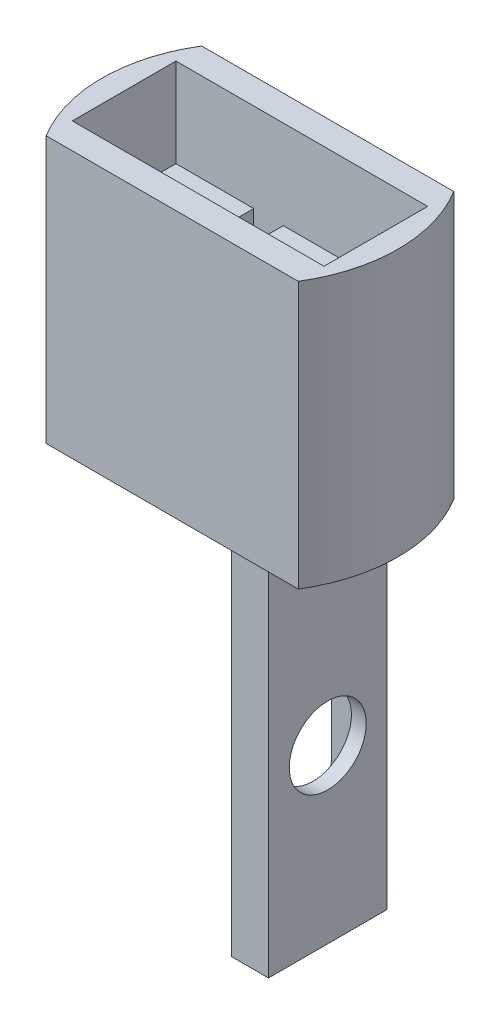
SolidWorks part; units mm, degrees
ref_plane "Front Plane" through (0, 0, 0) normal (0, 0, 1) x (1, 0, 0)
ref_plane "Top Plane" through (0, 0, 0) normal (0, 1, 0) x (1, 0, 0)
ref_plane "Right Plane" through (0, 0, 0) normal (1, 0, 0) x (0, 0, -1)
sketch "Sketch3" plane through (0, 0, 0) normal (0, 1, 0) x (1, 0, 0)
  circle A0 centre (0, 0) radius 10
  dimension "D1" = 20
extrude "Boss-Extrude1" add sketch "Sketch3" along normal blind 18
sketch "Sketch4" plane through (0, 0, 0) normal (0, -1, 0) x (-1, 0, 0)
  line L1 (-2.75, 4) -> (-5.25, 4)
  line L2 (-2.75, 4) -> (-2.75, -4)
  line L3 (-2.75, -4) -> (-5.25, -4)
  line L4 (-5.25, 4) -> (-5.25, -4)
  line L5 (-2.75, 4) -> (-5.25, -4) construction
  line L6 (-2.75, -4) -> (-5.25, 4) construction
  point P0 (-4, 0)
  dimension "D1" = 2.5
  dimension "D2" = 8
  dimension "D3" = 4
extrude "Boss-Extrude2" add sketch "Sketch4" along normal blind 25
sketch "Sketch5" plane through (5.25, 0, 0) normal (1, 0, 0) x (0, 0, -1)
  line L3 (-4, -25) -> (4, -25) construction
  circle A0 centre (0, -13.4) radius 2.6
  dimension "D1" = 5.2
  dimension "D2" = 11.6
extrude "Cut-Extrude1" cut sketch "Sketch5" against normal up to next
sketch "Sketch6" plane through (2.75, 0, 0) normal (-1, 0, 0) x (0, 0, 1)
  line L1 (-2.75, -23.9) -> (2.75, -23.9)
  line L2 (-2.75, -23.9) -> (-2.75, -2.9)
  line L3 (-2.75, -2.9) -> (2.75, -2.9)
  line L4 (2.75, -23.9) -> (2.75, -2.9)
  line L5 (-2.75, -23.9) -> (2.75, -2.9) construction
  line L6 (-2.75, -2.9) -> (2.75, -23.9) construction
  point P0 (0, -13.4)
  dimension "D1" = 21
  dimension "D2" = 5.5
extrude "Cut-Extrude2" cut sketch "Sketch6" against normal blind 1.5
sketch "Sketch7" plane through (0, 18, 0) normal (0, 1, 0) x (1, 0, 0)
  line L0 (-10, 0) -> (10, 0) construction
  line L1 (-8.5, -3.5) -> (8.5, -3.5)
  line L2 (-8.5, -3.5) -> (-8.5, 3.5)
  line L3 (-8.5, 3.5) -> (8.5, 3.5)
  line L4 (8.5, -3.5) -> (8.5, 3.5)
  circle A0 centre (0, 0) radius 10 construction
  point P4 (-8.5, 0)
  dimension "D1" = 7
  dimension "D2" = 17
  dimension "D3" = 1.5
extrude "Cut-Extrude3" cut sketch "Sketch7" against normal blind 6
sketch "Sketch8" plane through (0, 12, 0) normal (0, 1, 0) x (1, 0, 0)
  line L0 (8.5, 0) -> (-1.25, 0) construction
  line L1 (8.5, -3.5) -> (8.5, 3.5) construction
  line L2 (8.5, 3.5) -> (-8.5, 3.5) construction
  line L3 (-1.25, 3.5) -> (-3.25, 3.5)
  line L4 (-1.25, 3.5) -> (-1.25, -3.5)
  line L5 (-1.25, -3.5) -> (-3.25, -3.5)
  line L6 (-3.25, 3.5) -> (-3.25, -3.5)
  line L7 (-8.5, 3.5) -> (-8.5, -3.5) construction
  dimension "D1" = 9.75
  dimension "D2" = 2
extrude "Cut-Extrude4" cut sketch "Sketch8" against normal blind 4
sketch "Sketch9" plane through (4.25, 0, 0) normal (-1, 0, 0) x (0, 0, 1)
  line L0 (-2.75, -23.9) -> (-2.75, -16.9)
  line L1 (-2.75, -2.9) -> (-2.75, -23.9) construction
  line L2 (-2.75, -16.9) -> (-1.5, -23.9)
  line L3 (-2.75, -23.9) -> (2.75, -23.9) construction
  line L4 (-1.5, -23.9) -> (-2.75, -23.9)
  line L6 (-2.75, -13.4) -> (2.75, -13.4) construction
  line L7 (2.75, -23.9) -> (2.75, -2.9) construction
  line L8 (0, -23.9) -> (0, -2.9) construction
  line L9 (2.75, -2.9) -> (-2.75, -2.9) construction
  line L10 (1.5, -23.9) -> (2.75, -23.9)
  line L11 (2.75, -16.9) -> (1.5, -23.9)
  line L12 (2.75, -23.9) -> (2.75, -16.9)
  line L13 (2.75, -2.9) -> (2.75, -9.9)
  line L14 (2.75, -9.9) -> (1.5, -2.9)
  line L15 (1.5, -2.9) -> (2.75, -2.9)
  line L16 (-1.5, -2.9) -> (-2.75, -2.9)
  line L17 (-2.75, -9.9) -> (-1.5, -2.9)
  line L18 (-2.75, -2.9) -> (-2.75, -9.9)
  dimension "D1" = 1.25
  dimension "D2" = 7
extrude "Boss-Extrude3" add sketch "Sketch9" along normal up to surface (1.5 mm away) up to face at (2.75, -13.4, 0)
ref_plane "Plane1" through (4.25, -23.9, -1.5) normal (1, 0, 0) x (0, 0, -1)
sketch "Sketch11" plane through (0, 0, 0) normal (0, -1, 0) x (-1, 0, 0)
  line L0 (8.511, 5.25) -> (-8.511, 5.25)
  line L1 (0, 5.25) -> (0, 10) construction
  line L2 (-2.75, 4) -> (-5.25, 4) construction
  line L3 (0, 0) -> (-10, 0) construction
  line L4 (-10, 0) -> (10, 0) construction
  line L5 (8.511, -5.25) -> (-8.511, -5.25)
  arc A0 (-8.511, 5.25) -> (8.511, 5.25) centre (0, 0) cw
  circle A1 centre (0, 0) radius 10 construction
  arc A2 (-8.511, -5.25) -> (8.511, -5.25) centre (0, 0) ccw
  dimension "D1" = 1.25
extrude "Cut-Extrude5" cut sketch "Sketch11" against normal up to next
